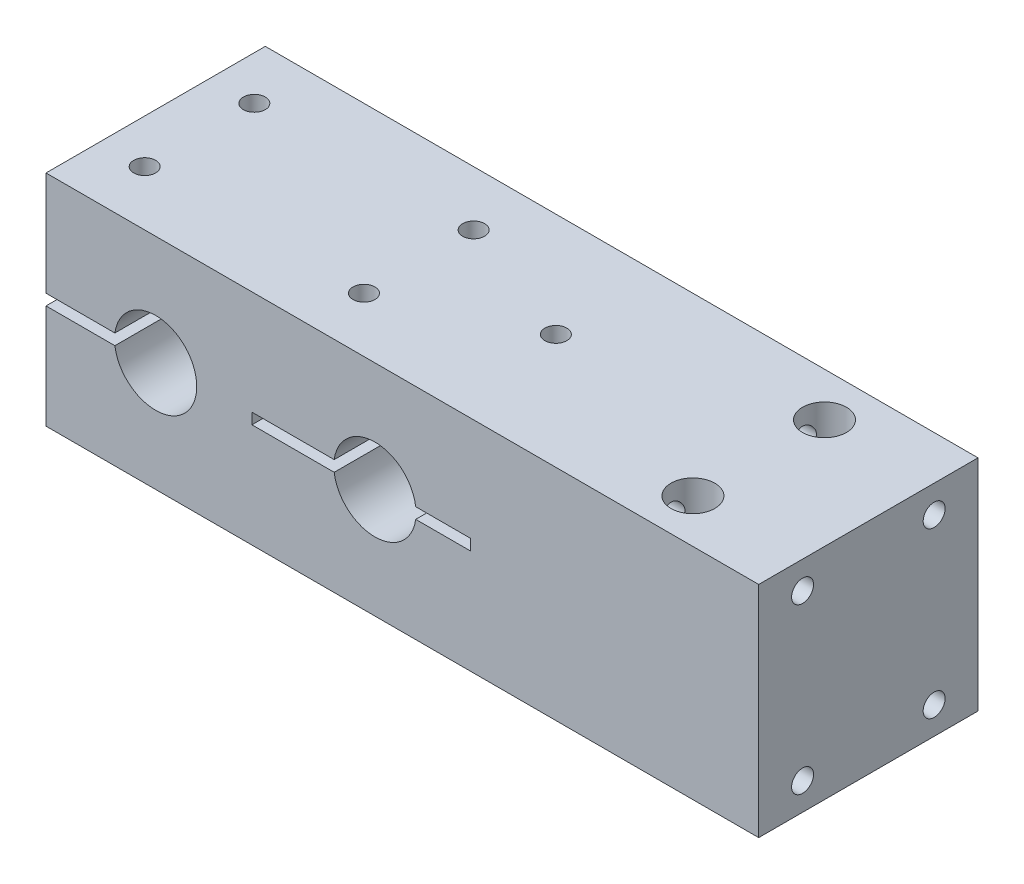
SolidWorks part; units mm, degrees
material "Сосна"
ref_plane "Спереди" through (0, 0, 0) normal (0, 0, 1) x (1, 0, 0)
ref_plane "Сверху" through (0, 0, 0) normal (0, 1, 0) x (1, 0, 0)
ref_plane "Справа" through (0, 0, 0) normal (1, 0, 0) x (0, 0, -1)
sketch "Эскиз1" plane through (0, 0, 0) normal (0, 0, 1) x (1, 0, 0)
  line L0 (67.433, 21) -> (77.433, 21)
  line L1 (0, 0) -> (130, 0)
  line L2 (0, 0) -> (0, 19)
  line L3 (0, 40) -> (130, 40)
  line L4 (130, 40) -> (130, 0)
  line L5 (67.433, 19) -> (77.433, 19)
  line L6 (0, 21) -> (12.567, 21)
  line L7 (77.433, 21) -> (77.433, 19)
  line L8 (0, 19) -> (12.567, 19)
  line L9 (0, 21) -> (0, 40)
  line L10 (37.567, 21) -> (52.567, 21)
  line L11 (37.567, 19) -> (52.567, 19)
  line L12 (37.567, 21) -> (37.567, 19)
  arc A0 (12.567, 19) -> (12.567, 21) centre (20, 20) ccw
  arc A1 (67.433, 21) -> (52.567, 21) centre (60, 20) ccw
  arc A2 (52.567, 19) -> (67.433, 19) centre (60, 20) ccw
  dimension "D5" = 19
  dimension "D4" = 20
  dimension "D6" = 20
  dimension "D8" = 7.5
  dimension "D9" = 7.5
  dimension "D12" = 40
  dimension "D7" = 40
  dimension "D1" = 130
  dimension "D2" = 40
  dimension "D3" = 2
  dimension "D10" = 10
  dimension "D11" = 20
  dimension "D13" = 10
  dimension "D15" = 15
  dimension "D16" = 15
  dimension "D17" = 2
extrude "Бобышка-Вытянуть1" add sketch "Эскиз1" along normal blind 40
sketch "Эскиз8" plane through (0, 0, 0) normal (0, -1, 0) x (1, 0, 0)
  line L0 (0, 40) -> (0, 0) construction
  line L1 (0, 40) -> (130, 40) construction
  line L2 (0, 0) -> (130, 0) construction
  line L14 (0, 40) -> (0, 0)
  circle A0 centre (8, 30) radius 2
  circle A1 centre (8, 10) radius 2
  circle A4 centre (48, 30) radius 2
  circle A5 centre (48, 10) radius 2
  dimension "D1" = 8
  dimension "D3" = 10
  dimension "D5" = 40
  dimension "D6" = 40
  dimension "D2" = 10
  dimension "D4" = 8
extrude "Вырез-Вытянуть1" cut sketch "Эскиз8" against normal blind 50
sketch "Эскиз9" plane through (130, 0, 0) normal (1, 0, 0) x (0, 0, -1)
  line L0 (-40, 40) -> (0, 40) construction
  line L1 (-8, 35) -> (-32, 35)
  line L2 (-8, 35) -> (-8, 5)
  line L3 (-8, 5) -> (-32, 5)
  line L4 (-32, 35) -> (-32, 5)
  line L5 (0, 0) -> (0, 40) construction
  circle A0 centre (-32, 35) radius 2
  circle A1 centre (-8, 35) radius 2
  circle A2 centre (-8, 5) radius 2
  circle A3 centre (-32, 5) radius 2
  dimension "D5" = 4
  dimension "D6" = 4
  dimension "D7" = 4
  dimension "D8" = 4
  dimension "D1" = 24
  dimension "D2" = 30
  dimension "D3" = 5
  dimension "D4" = 8
extrude "Вырез-Вытянуть2" cut sketch "Эскиз9" against normal blind 30 contours A0 | A1 | A2 | A3
sketch "Эскиз10" plane through (0, 40, 0) normal (0, 1, 0) x (1, 0, 0)
  line L0 (130, -40) -> (130, 0) construction
  line L1 (130, 0) -> (0, 0) construction
  line L2 (130, -40) -> (0, -40) construction
  circle A0 centre (110, -8) radius 4.0006
  circle A1 centre (110, -32) radius 4
  dimension "D1" = 20
  dimension "D2" = 20
  dimension "D3" = 8
  dimension "D4" = 8
extrude "Вырез-Вытянуть3" cut sketch "Эскиз10" against normal blind 10
sketch "Эскиз11" plane through (0, 0, 0) normal (0, -1, 0) x (1, 0, 0)
  line L0 (130, 40) -> (130, 0) construction
  line L1 (0, 0) -> (130, 0) construction
  line L2 (0, 40) -> (130, 40) construction
  circle A0 centre (110, 32) radius 4
  circle A1 centre (110, 8) radius 4
  dimension "D1" = 20
  dimension "D2" = 20
  dimension "D3" = 8
  dimension "D4" = 8
extrude "Вырез-Вытянуть4" cut sketch "Эскиз11" against normal blind 10
sketch "Эскиз12" plane through (0, 0, 0) normal (0, -1, 0) x (1, 0, 0)
  line L0 (72, 40) -> (72, 0) construction
  line L1 (0, 40) -> (130, 40) construction
  line L2 (0, 0) -> (130, 0) construction
  line L3 (130, 40) -> (130, 0) construction
  circle A0 centre (72, 19) radius 2
  dimension "D2" = 4
  dimension "D1" = 58
  dimension "D3" = 19
extrude "Вырез-Вытянуть5" cut sketch "Эскиз12" against normal blind 40
